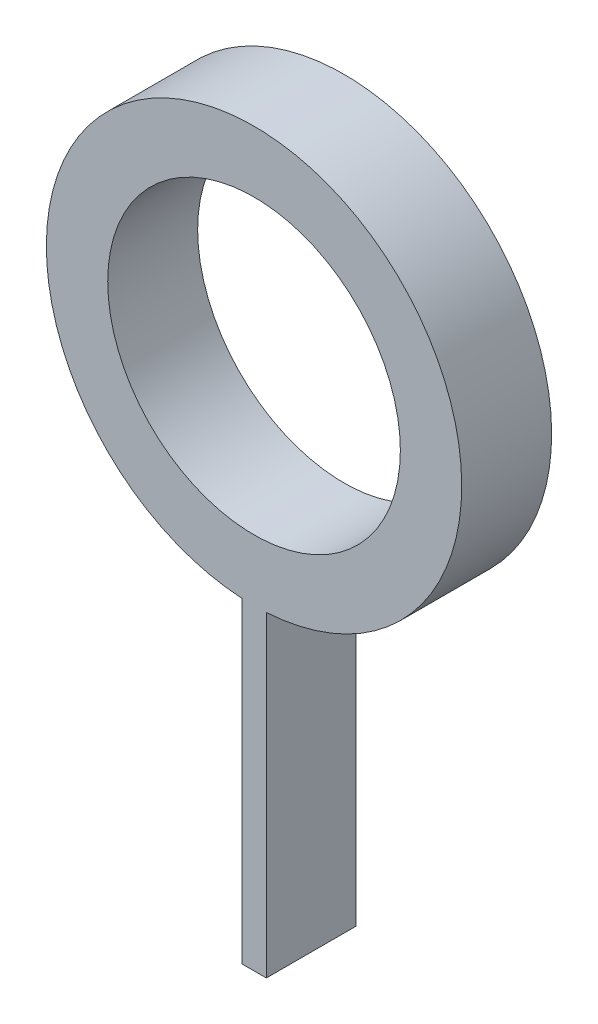
SolidWorks part; units mm, degrees
material "Brass"
ref_plane "Front" through (0, 0, 0) normal (0, 0, 1) x (1, 0, 0)
ref_plane "Top" through (0, 0, 0) normal (0, 1, 0) x (1, 0, 0)
ref_plane "Right" through (0, 0, 0) normal (1, 0, 0) x (0, 0, -1)
sketch "Sketch1" plane through (0, 0, 0) normal (0, 0, 1) x (1, 0, 0)
  line L0 (0, -7.75) -> (0, -27.75)
  line L2 (-0.65, -27.75) -> (0.65, -27.75)
  line L3 (-0.65, -27.75) -> (-0.65, -7.75)
  line L4 (-0.65, -7.75) -> (0.65, -7.75)
  line L5 (0.65, -27.75) -> (0.65, -7.75)
  circle A0 centre (0, 0) radius 11
  circle A1 centre (0, 0) radius 7.75
  point P10 (0, -7.75)
  point P13 (0, -27.75)
  dimension "D1" = 22
  dimension "D2" = 15.5
  dimension "D3" = 1.3
  dimension "D4" = 20
extrude "Boss-Extrude1" add sketch "Sketch1" along normal blind 4.7625 contours L4 A1 L5 A0 L3 | L0 A0 L5 L4 | L3 A0 L0 L4 | A0 L3 L2 L0 | A0 L0 L2 L5
